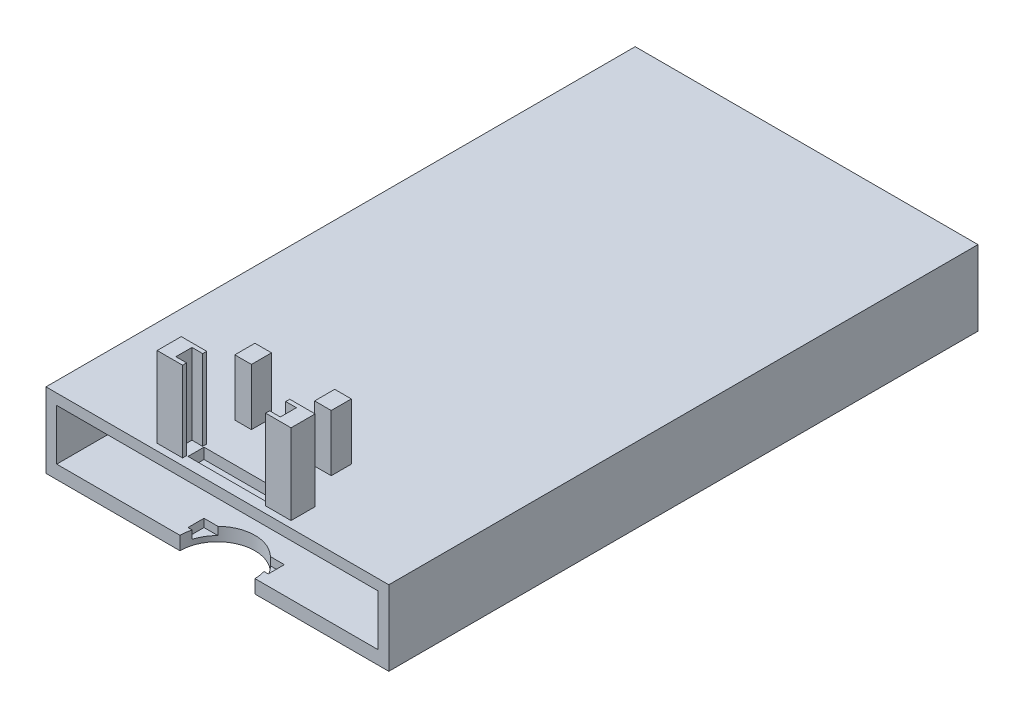
SolidWorks part; units mm, degrees
ref_plane "Plan de face" through (0, 0, 0) normal (0, 0, 1) x (1, 0, 0)
ref_plane "Plan de dessus" through (0, 0, 0) normal (0, 1, 0) x (1, 0, 0)
ref_plane "Plan de droite" through (0, 0, 0) normal (1, 0, 0) x (0, 0, -1)
sketch "Esquisse1" plane through (0, 0, 0) normal (0, 0, 1) x (1, 0, 0)
  line L1 (-64, 0) -> (64, 0)
  line L2 (-64, 0) -> (-64, 28)
  line L3 (-64, 28) -> (64, 28)
  line L4 (64, 0) -> (64, 28)
  line L6 (-60, 5) -> (60, 5)
  line L7 (-60, 5) -> (-60, 24)
  line L8 (-60, 24) -> (60, 24)
  line L9 (60, 5) -> (60, 24)
extrude "Corps_casier" add sketch "Esquisse1" against normal blind 220
sketch "Esquisse2" plane through (0, 0, 0) normal (0, 0, 1) x (1, 0, 0)
  line L1 (-60, 5) -> (60, 5)
  line L2 (-60, 5) -> (-60, 24)
  line L3 (-60, 24) -> (60, 24)
  line L4 (60, 5) -> (60, 24)
  line L6 (-10.5, 8.5) -> (10.5, 8.5)
  line L7 (-10.5, 8.5) -> (-10.5, 19.5)
  line L8 (-10.5, 19.5) -> (10.5, 19.5)
  line L9 (10.5, 8.5) -> (10.5, 19.5)
extrude "Paroi_fond" add sketch "Esquisse2" against normal blind 5 from offset 215
sketch "Esquisse3" plane through (0, 0, 0) normal (1, 0, 0) x (0, 0, -1)
  line L1 (4, 23) -> (10, 23)
  line L2 (4, 23) -> (4, 29)
  line L3 (4, 29) -> (10, 29)
  line L4 (10, 23) -> (10, 29)
  line L6 (4, 2) -> (10, 2)
  line L7 (4, 2) -> (4, 6)
  line L8 (4, 6) -> (10, 6)
  line L9 (10, 2) -> (10, 6)
extrude "Fente_et_encoche_verrou" cut sketch "Esquisse3" against normal mid plane 30
sketch "Esquisse4" plane through (0, 0, 0) normal (0, 1, 0) x (1, 0, 0)
  circle A0 centre (0, 0) radius 14
extrude "Encoche_prise_doigt" cut sketch "Esquisse4" along normal blind 6
sketch "Esquisse5" plane through (0, 0, 0) normal (0, 1, 0) x (1, 0, 0)
  line L0 (-25, 2.5) -> (-15.5, 2.5)
  line L1 (-15.5, 2.5) -> (-15.5, 4)
  line L2 (-15.5, 4) -> (-19.5, 4)
  line L3 (-19.5, 4) -> (-19.5, 10)
  line L4 (-19.5, 10) -> (-15.5, 10)
  line L5 (-15.5, 10) -> (-15.5, 11.5)
  line L6 (-15.5, 11.5) -> (-25, 11.5)
  line L7 (-25, 11.5) -> (-25, 2.5)
  line L8 (25, 2.5) -> (15.5, 2.5)
  line L9 (15.5, 2.5) -> (15.5, 4)
  line L10 (15.5, 4) -> (19.5, 4)
  line L11 (19.5, 4) -> (19.5, 10)
  line L12 (19.5, 10) -> (15.5, 10)
  line L13 (15.5, 10) -> (15.5, 11.5)
  line L14 (15.5, 11.5) -> (25, 11.5)
  line L15 (25, 11.5) -> (25, 2.5)
extrude "Glissieres_verrou" add sketch "Esquisse5" along normal blind 30 from offset 28
sketch "Esquisse6" plane through (0, 0, 0) normal (0, 1, 0) x (1, 0, 0)
  line L1 (-18, 24.5) -> (-11.8, 24.5)
  line L2 (-18, 24.5) -> (-18, 32)
  line L3 (-18, 32) -> (-11.8, 32)
  line L4 (-11.8, 24.5) -> (-11.8, 32)
  line L6 (11.8, 24.5) -> (18, 24.5)
  line L7 (11.8, 24.5) -> (11.8, 32)
  line L8 (11.8, 32) -> (18, 32)
  line L9 (18, 24.5) -> (18, 32)
extrude "Supports_servo_SG90" add sketch "Esquisse6" along normal blind 21.1 from offset 28
